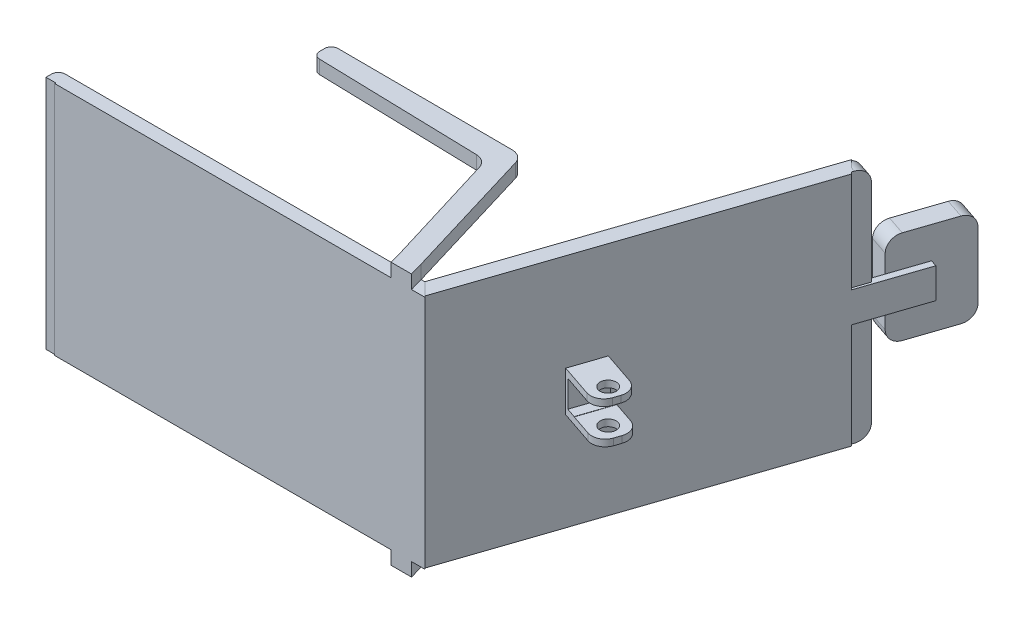
SolidWorks part; units mm, degrees
ref_plane "Front Plane" through (0, 0, 0) normal (0, 0, 1) x (1, 0, 0)
ref_plane "Top Plane" through (0, 0, 0) normal (0, 1, 0) x (1, 0, 0)
ref_plane "Right Plane" through (0, 0, 0) normal (1, 0, 0) x (0, 0, -1)
sketch "Sketch1" plane through (0, 0, 0) normal (0, 0, 1) x (1, 0, 0)
  line L1 (0, 0) -> (549.87, 0)
  line L2 (0, 0) -> (0, 349.87)
  line L3 (0, 349.87) -> (549.87, 349.87)
  line L4 (549.87, 0) -> (549.87, 349.87)
  dimension "D1" = 549.87
  dimension "D2" = 349.87
extrude "Boss-Extrude1" add sketch "Sketch1" along normal blind 20
sketch "Sketch5" plane through (0, 0, 0) normal (0, -1, 0) x (1, 0, 0)
  line L0 (549.87, 20) -> (549.87, 0)
  line L1 (549.87, 0) -> (529.87, 0)
  line L2 (0, 0) -> (549.87, 0) construction
  line L3 (529.87, 0) -> (549.87, 20)
extrude "Cut-Extrude1" cut sketch "Sketch5" against normal blind 390
sketch "Sketch6" plane through (264.935, 0, -264.935) normal (0.7071, 0, -0.7071) x (-0.7071, 0, -0.7071)
  line L0 (-402.9589, 0) -> (-374.6747, 0)
sketch "Sketch7" plane through (0, 0, 0) normal (0, 1, 0) x (1, 0, 0)
  line L0 (548.2477, -18.3777) -> (529.87, 0)
  line L1 (549.87, -20) -> (529.87, 0) construction
  line L2 (529.87, 0) -> (689.7292, 473.7563)
  line L3 (689.7292, 473.7563) -> (708.1886, 455.2969)
  line L4 (708.1886, 455.2969) -> (548.2477, -18.3777)
  dimension "D1" = 500
extrude "Boss-Extrude2" add sketch "Sketch7" along normal blind 350
sketch "Sketch8" plane through (497.7074, 0, 168.0558) normal (0.9474, 0, 0.3199) x (0.3199, 0, -0.9474)
  line L0 (657.9293, 350) -> (657.9293, 0)
  line L10 (621.0285, 201.0251) -> (756.6389, 201.0251)
  line L11 (621.0285, 201.0251) -> (621.0285, 156.0251)
  line L12 (621.0285, 156.0251) -> (756.6389, 156.0251)
  line L13 (756.6389, 201.0251) -> (756.6389, 156.0251)
  point P3 (657.9293, 175)
  dimension "D1" = 45
extrude "Boss-Extrude3" add sketch "Sketch8" against normal blind 10 contours L13 L10 L0 L12 | L11 L12 L0 L10
sketch "Sketch9" plane through (488.2329, 0, 164.8567) normal (-0.9474, 0, -0.3199) x (-0.3199, 0, 0.9474)
  line L5 (-756.6389, 201.0251) -> (-756.6389, 156.0251) construction
  line L6 (-791.0208, 109.23) -> (-722.2569, 109.23)
  line L7 (-811.0208, 129.23) -> (-811.0208, 227.8202)
  line L8 (-791.0208, 247.8202) -> (-722.2569, 247.8202)
  line L9 (-702.2569, 129.23) -> (-702.2569, 227.8202)
  line L10 (-811.0208, 109.23) -> (-702.2569, 247.8202) construction
  line L11 (-811.0208, 247.8202) -> (-702.2569, 109.23) construction
  arc A0 (-702.2569, 129.23) -> (-722.2569, 109.23) centre (-722.2569, 129.23) cw
  arc A1 (-791.0208, 109.23) -> (-811.0208, 129.23) centre (-791.0208, 129.23) cw
  arc A2 (-722.2569, 247.8202) -> (-702.2569, 227.8202) centre (-722.2569, 227.8202) cw
  arc A3 (-791.0208, 247.8202) -> (-811.0208, 227.8202) centre (-791.0208, 227.8202) ccw
  point P0 (-756.6389, 178.5251)
  dimension "D1" = 20
extrude "Boss-Extrude4" add sketch "Sketch9" along normal blind 30
sketch "Sketch10" plane through (475.7068, 0, 160.5173) normal (-0.9475, 0, -0.3197) x (-0.3197, 0, 0.9475)
  line L5 (-169.4092, 0) -> (-662.7342, 0)
  line L6 (-169.4092, 0) -> (-169.4092, 350)
  line L7 (-169.4092, 350) -> (-662.7342, 350)
  line L8 (-682.7342, 20) -> (-682.7342, 330)
  arc A0 (-662.7342, 0) -> (-682.7342, 20) centre (-662.7342, 20) cw
  arc A1 (-662.7342, 350) -> (-682.7342, 330) centre (-662.7342, 330) ccw
  point P0 (-669.4092, 350)
  dimension "D1" = 20
extrude "Boss-Extrude5" add sketch "Sketch10" against normal blind 20
sketch "Sketch12" plane through (0, 349.87, 0) normal (0, 1, 0) x (1, 0, 0)
  line L1 (548.2477, -18.3777) -> (-14.5959, -18.3777)
  line L2 (548.2477, -18.3777) -> (548.2477, 0)
  line L3 (548.2477, 0) -> (-4.5959, 0)
  line L4 (-14.5959, -18.3777) -> (-14.5959, -10)
  arc A0 (-4.5959, 0) -> (-14.5959, -10) centre (-4.5959, -10) ccw
  dimension "D1" = 10
extrude "Boss-Extrude6" add sketch "Sketch12" against normal blind 350
sketch "Sketch13" plane through (0, 0, 0) normal (0, 1, 0) x (1, 0, 0)
  line L0 (529.87, -20) -> (466.9205, 203.866)
  line L1 (549.87, -20) -> (0, -20) construction
  line L2 (447.6672, 218.4521) -> (182.3535, 218.4521)
  line L3 (172.3535, 208.4521) -> (172.3535, 195.4447)
  line L4 (182.3535, 185.4447) -> (426.7624, 185.4447)
  line L5 (446.0158, 170.8586) -> (499.6838, -20)
  line L6 (499.6838, -20) -> (529.87, -20)
  arc A0 (172.3535, 195.4447) -> (182.3535, 185.4447) centre (182.3535, 195.4447) ccw
  arc A1 (172.3535, 208.4521) -> (182.3535, 218.4521) centre (182.3535, 208.4521) cw
  arc A2 (426.7624, 185.4447) -> (446.0158, 170.8586) centre (426.7624, 165.4447) cw
  arc A3 (466.9205, 203.866) -> (447.6672, 218.4521) centre (447.6672, 198.4521) ccw
  dimension "D1" = 10
  dimension "D2" = 20
  dimension "D3" = 265.3137
  dimension "D4" = 190.8586
extrude "Boss-Extrude8" add sketch "Sketch13" against normal blind 20
sketch "Sketch14" plane through (0, 349.87, 0) normal (0, 1, 0) x (1, 0, 0)
  line L0 (494.06, 0) -> (524.2461, 0)
  line L1 (524.2461, 0) -> (464.0103, 200.2148)
  line L2 (444.9377, 214.4527) -> (185.3221, 215.4833)
  line L3 (175.2824, 205.4834) -> (175.2824, 198.112)
  line L4 (185.0174, 188.1155) -> (424.4338, 181.7684)
  line L5 (443.0368, 167.6001) -> (494.06, 0)
  line L6 (494.06, 0) -> (524.2461, 0)
  arc A0 (466.9205, 203.866) -> (447.6672, 218.4521) centre (447.6672, 198.4521) ccw construction
  arc A1 (182.3535, 218.4521) -> (172.3535, 208.4521) centre (182.3535, 208.4521) ccw construction
  arc A2 (172.3535, 195.4447) -> (182.3535, 185.4447) centre (182.3535, 195.4447) ccw construction
  arc A3 (446.0158, 170.8586) -> (426.7624, 185.4447) centre (426.7624, 165.4447) ccw construction
  arc A4 (175.2824, 205.4834) -> (185.3221, 215.4833) centre (185.2824, 205.4834) cw
  arc A5 (175.2824, 198.112) -> (185.0174, 188.1155) centre (185.2824, 198.112) ccw
  arc A6 (443.0368, 167.6001) -> (424.4338, 181.7684) centre (423.9037, 161.7754) ccw
  arc A7 (464.0103, 200.2148) -> (444.9377, 214.4527) centre (444.8583, 194.4528) ccw
  point P22 (175.2824, 215.5232)
  point P25 (175.2824, 188.3736)
  point P28 (438.8397, 181.3864)
  point P31 (459.7445, 214.3939)
  line M13 (529.87, 0) -> (-4.5959, 0)
  dimension "D1" = 10
  dimension "D2" = 20
extrude "Boss-Extrude9" add sketch "Sketch14" along normal blind 20 separate body contours L1 A7 L2 A4 L3 A5 L4 A6 L5 M13
sketch "Sketch15" plane through (0, 349.87, 0) normal (0, 1, 0) x (1, 0, 0)
  line L0 (494.06, 0) -> (499.6838, -20)
  line L1 (499.6838, -20) -> (529.87, -20)
  line L2 (549.87, -20) -> (0, -20) construction
  line L5 (524.2461, 0) -> (494.06, 0)
  line L6 (524.2461, 0) -> (529.87, -20)
extrude "Boss-Extrude10" add sketch "Sketch15" along normal blind 20
sketch "Sketch17" plane through (497.7074, 0, 168.0558) normal (0.9474, 0, 0.3199) x (0.3199, 0, -0.9474)
  line L0 (157.9806, 349.87) -> (156.9625, 0)
  line L3 (322.9046, 145.422) -> (372.9046, 145.422)
  line L4 (322.9046, 145.422) -> (322.9046, 205.422)
  line L5 (322.9046, 205.422) -> (372.9046, 205.422)
  line L6 (372.9046, 145.422) -> (372.9046, 205.422)
  dimension "D1" = 60
  dimension "D2" = 50
extrude "Boss-Extrude11" add sketch "Sketch17" along normal blind 20 contours L3 L6 L5 L4
sketch "Sketch27" plane through (0, 145.422, 0) normal (0, -1, 0) x (-1, 0, 0)
  line L0 (-619.9582, 131.4807) -> (-651.0093, 120.996)
  line L1 (-676.3565, 133.5466) -> (-679.5557, 143.0211)
  line L2 (-667.005, 168.3683) -> (-635.954, 178.853)
  line L3 (-619.9582, 131.4807) -> (-635.954, 178.853)
  arc A0 (-667.005, 168.3683) -> (-679.5557, 143.0211) centre (-660.6067, 149.4194) ccw
  arc A1 (-676.3565, 133.5466) -> (-651.0093, 120.996) centre (-657.4076, 139.9449) ccw
  point P8 (-685.954, 161.97)
  point P11 (-669.9582, 114.5977)
  dimension "D3" = 20
  dimension "D1" = 50
  dimension "D2" = 50
extrude "Boss-Extrude12" add sketch "Sketch27" against normal blind 10
sketch "Sketch28" plane through (0, 205.422, 0) normal (0, 1, 0) x (1, 0, 0)
  line L0 (635.954, 178.853) -> (664.3773, 169.2556)
  line L1 (676.928, 143.9084) -> (673.7288, 134.4339)
  line L2 (648.3816, 121.8833) -> (619.9582, 131.4807)
  line L3 (619.9582, 131.4807) -> (635.954, 178.853)
  arc A0 (676.928, 143.9084) -> (664.3773, 169.2556) centre (657.9791, 150.3066) ccw
  arc A1 (673.7288, 134.4339) -> (648.3816, 121.8833) centre (654.7799, 140.8322) cw
  point P8 (683.3263, 162.8573)
  point P11 (667.3305, 115.485)
  dimension "D4" = 20
  dimension "D1" = 50
  dimension "D2" = 50
  dimension "D3" = 50
extrude "Boss-Extrude13" add sketch "Sketch28" against normal blind 10
sketch "Sketch29" plane through (516.6563, 0, 174.4541) normal (0.9474, 0, 0.3199) x (0.3199, 0, -0.9474)
  line L0 (372.9046, 145.422) -> (372.9046, 205.422) construction
  line L1 (322.9046, 195.422) -> (372.9046, 195.422)
  line L2 (322.9046, 195.422) -> (322.9046, 155.7615)
  line L3 (322.9046, 155.7615) -> (372.9046, 155.7615)
  line L4 (372.9046, 195.422) -> (372.9046, 155.7615)
extrude "Cut-Extrude2" cut sketch "Sketch29" against normal blind 15
sketch "Sketch30" plane through (0, 205.422, 0) normal (0, 1, 0) x (1, 0, 0)
  line L0 (675.3284, 139.1711) -> (609.0072, 161.5651)
  line L1 (673.7288, 134.4339) -> (676.928, 143.9084) construction
  line L2 (601.0093, 137.879) -> (617.005, 185.2513) construction
  line L3 (609.0072, 161.5651) -> (617.005, 185.2513)
  line L4 (548.2477, -18.3777) -> (708.1886, 455.2969) construction
  line L5 (617.005, 185.2513) -> (664.3773, 169.2556)
  line L6 (664.3773, 169.2556) -> (648.3816, 121.8833)
  line L7 (648.3816, 121.8833) -> (601.0093, 137.879) construction
  circle A1 centre (656.3795, 145.5694) radius 12
extrude "Cut-Extrude4" cut sketch "Sketch30" against normal blind 135 contours L0 A1 L6 | L6 A1 L0 | L0 A1 L6 | L6 A1 L0
sketch "Sketch42" plane through (475.7068, 0, 160.5173) normal (-0.9475, 0, -0.3197) x (-0.3197, 0, 0.9475)
  text T0 "COLLEGE TEAM" font "Comic Sans MS" height in points 72
extrude "Boss-Extrude14" add sketch "Sketch42" along normal blind 15
